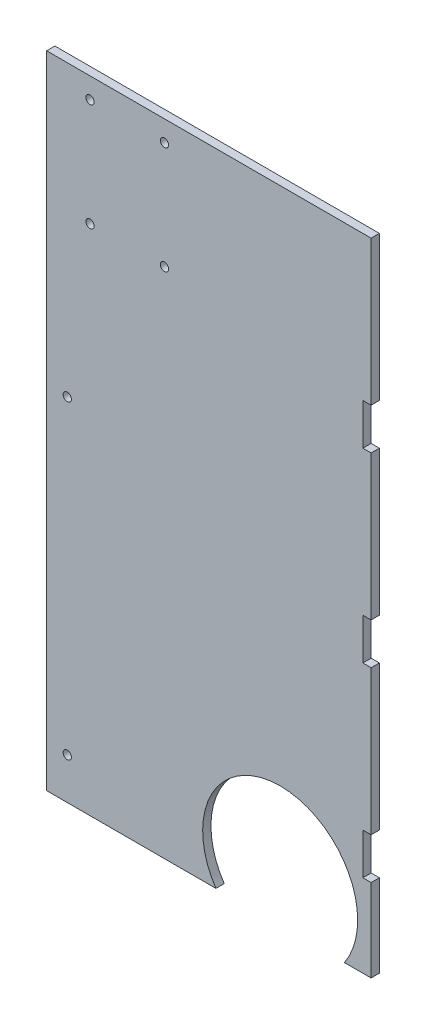
SolidWorks part; units mm, degrees
ref_plane "Front Plane" through (0, 0, 0) normal (0, 0, 1) x (1, 0, 0)
ref_plane "Top Plane" through (0, 0, 0) normal (0, 1, 0) x (1, 0, 0)
ref_plane "Right Plane" through (0, 0, 0) normal (1, 0, 0) x (0, 0, -1)
sketch "Sketch1" plane through (0, 0, 0) normal (0, 0, 1) x (1, 0, 0)
  line L1 (-75, 150) -> (90, 150)
  line L2 (-75, 150) -> (-75, -180)
  line L3 (-75, -180) -> (90, -180)
  line L4 (90, 150) -> (90, -180)
  line L5 (-75, 150) -> (90, -180) construction
  line L6 (-75, -180) -> (90, 150) construction
  point P0 (0, 0)
  dimension "D1" = 165
extrude "Boss-Extrude1" add sketch "Sketch1" along normal blind 4
sketch "Sketch2" plane through (0, 0, 4) normal (0, 0, 1) x (1, 0, 0)
  circle A0 centre (38, -159) radius 37.5
  dimension "D1" = 75
extrude "Cut-Extrude1" cut sketch "Sketch2" against normal through all
sketch "Sketch4" plane through (0, 0, 0) normal (0, 0, -1) x (-1, 0, 0)
  line L1 (-90, 150) -> (-82, 150)
  line L2 (-90, 150) -> (-90, -150)
  line L3 (-90, -150) -> (-82, -150)
  line L4 (-82, 150) -> (-82, -150)
  dimension "D1" = 8
extrude "Cut-Extrude3" cut sketch "Sketch4" against normal through all
sketch "Sketch3" plane through (0, 0, 0) normal (0, 0, -1) x (-1, 0, 0)
  line L0 (-78, 150) -> (-78, 130)
  line L1 (-82, 150) -> (75, 150) construction
  line L2 (-78, 130) -> (-82, 130)
  line L4 (-78, 150) -> (-82, 150)
  line L5 (-82, 150) -> (-82, 130)
  line L6 (-78, 60) -> (-82, 60)
  line L7 (-78, 60) -> (-78, 40)
  line L8 (-78, 40) -> (-82, 40)
  line L9 (-82, 60) -> (-82, 40)
  line L10 (-78, -30) -> (-82, -30)
  line L11 (-78, -30) -> (-78, -50)
  line L12 (-78, -50) -> (-82, -50)
  line L13 (-82, -30) -> (-82, -50)
  line L14 (-78, -120) -> (-82, -120)
  line L15 (-78, -120) -> (-78, -140)
  line L16 (-78, -140) -> (-82, -140)
  line L17 (-82, -120) -> (-82, -140)
  line L18 (-82, -150) -> (-82, 150) construction
  dimension "D1" = 4
  dimension "D2" = 20
  dimension "D3" = 4
extrude "Cut-Extrude2" cut sketch "Sketch3" against normal through all
sketch "Sketch5" plane through (0, 0, 4) normal (0, 0, 1) x (1, 0, 0)
  line L0 (82, -150) -> (82, -180)
  line L1 (69.0685, -180) -> (90, -180) construction
  line L2 (82, -180) -> (90, -180)
  line L3 (90, -180) -> (90, -150)
  line L4 (90, -150) -> (82, -150)
extrude "Cut-Extrude4" cut sketch "Sketch5" against normal through all
sketch "Sketch6" plane through (0, 0, 0) normal (0, 0, -1) x (-1, 0, 0)
  line L0 (-78, 150) -> (75, 150) construction
  line L1 (-82, 60) -> (-82, 130) construction
  circle A0 centre (18, 120) radius 2
  circle A1 centre (54, 120) radius 2
  circle A2 centre (18, 68) radius 2
  circle A3 centre (54, 68) radius 2
  dimension "D1" = 4
  dimension "D2" = 36
  dimension "D3" = 52
  dimension "D4" = 30
  dimension "D5" = 100
extrude "Cut-Extrude5" cut sketch "Sketch6" against normal through all
sketch "Sketch7" plane through (0, 0, 4) normal (0, 0, 1) x (1, 0, 0)
  line L0 (-75, 150) -> (-75, -180) construction
  line L1 (78, 150) -> (-75, 150) construction
  circle A0 centre (-65, 140) radius 2
  circle A1 centre (-65, -10) radius 2
  circle A2 centre (-65, -160) radius 2
  dimension "D2" = 4
  dimension "D1" = 10
  dimension "D3" = 10
  dimension "D4" = 3
extrude "Cut-Extrude6" cut sketch "Sketch7" against normal through all
sketch "Sketch8" plane through (0, 0, 0) normal (0, 0, -1) x (-1, 0, 0)
  line L0 (75, 150) -> (75, -180) construction
  line L1 (-78, 150) -> (75, 150)
  line L2 (-78, 150) -> (-78, 130)
  line L3 (-78, 130) -> (75, 130)
  line L4 (75, 150) -> (75, 130)
  dimension "D1" = 20
extrude "Cut-Extrude7" cut sketch "Sketch8" against normal through all
